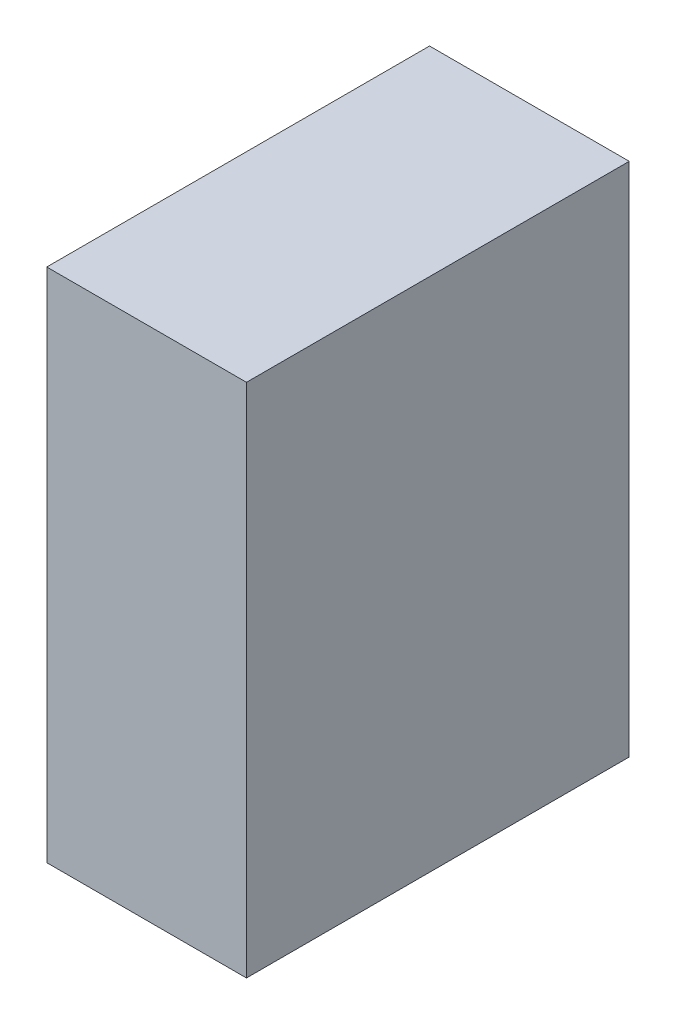
SolidWorks part; units mm, degrees
ref_plane "Front Plane" through (0, 0, 0) normal (0, 0, 1) x (1, 0, 0)
ref_plane "Top Plane" through (0, 0, 0) normal (0, 1, 0) x (1, 0, 0)
ref_plane "Right Plane" through (0, 0, 0) normal (1, 0, 0) x (0, 0, -1)
sketch "Sketch1" plane through (0, 0, 0) normal (1, 0, 0) x (0, 0, -1)
  line L1 (-41.0235, 72.9307) -> (105.0265, 72.9307)
  line L2 (-41.0235, 72.9307) -> (-41.0235, -123.9193)
  line L3 (-41.0235, -123.9193) -> (105.0265, -123.9193)
  line L4 (105.0265, 72.9307) -> (105.0265, -123.9193)
  dimension "D1" = 146.05
  dimension "D2" = 196.85
extrude "Boss-Extrude1" add sketch "Sketch1" along normal blind 76.2
sketch "Sketch2" plane through (0, -123.9193, 0) normal (0, -1, 0) x (1, 0, 0)
  circle A0 centre (15.96, 29.5535) radius 3.175 construction
  circle A1 centre (24.8421, 29.1795) radius 3.175 construction
  circle A2 centre (15.96, 29.5535) radius 3.175
  circle A3 centre (24.8421, 29.1795) radius 3.175
extrude "Cut-Extrude1" cut sketch "Sketch2" against normal blind 74.568
sketch "Sketch3" plane through (0, -123.9193, 0) normal (0, -1, 0) x (1, 0, 0)
  circle A0 centre (24.8406, 29.1454) radius 3.9688 construction
  circle A1 centre (15.96, 29.5535) radius 3.9688 construction
  circle A2 centre (24.8406, 29.1454) radius 3.9688
  circle A3 centre (15.96, 29.5535) radius 3.9688
extrude "Cut-Extrude2" cut sketch "Sketch3" against normal blind 50.568
sketch "Sketch4" plane through (0, -123.9193, 0) normal (0, -1, 0) x (1, 0, 0)
  circle A0 centre (30.46, -30.4465) radius 3.175 construction
  circle A1 centre (30.46, -30.4465) radius 3.175
extrude "Cut-Extrude3" cut sketch "Sketch4" against normal blind 38.268
sketch "Sketch5" plane through (0, -123.9193, 0) normal (0, -1, 0) x (1, 0, 0)
  circle A0 centre (30.46, -30.4465) radius 3.9688 construction
  circle A1 centre (30.46, -30.4465) radius 3.9688
extrude "Cut-Extrude4" cut sketch "Sketch5" against normal blind 6.268
sketch "Sketch6" plane through (0, 0, -105.0265) normal (0, 0, -1) x (-1, 0, 0)
  circle A0 centre (-20.96, -56.1513) radius 4 construction
  circle A1 centre (-20.96, 13.8487) radius 4 construction
  circle A2 centre (-20.96, -56.1513) radius 4
  circle A3 centre (-20.96, 13.8487) radius 4
extrude "Cut-Extrude5" cut sketch "Sketch6" against normal blind 13.08
sketch "Sketch7" plane through (0, 72.9307, 0) normal (0, 1, 0) x (1, 0, 0)
  point P0 (76.2, 105.0265)
